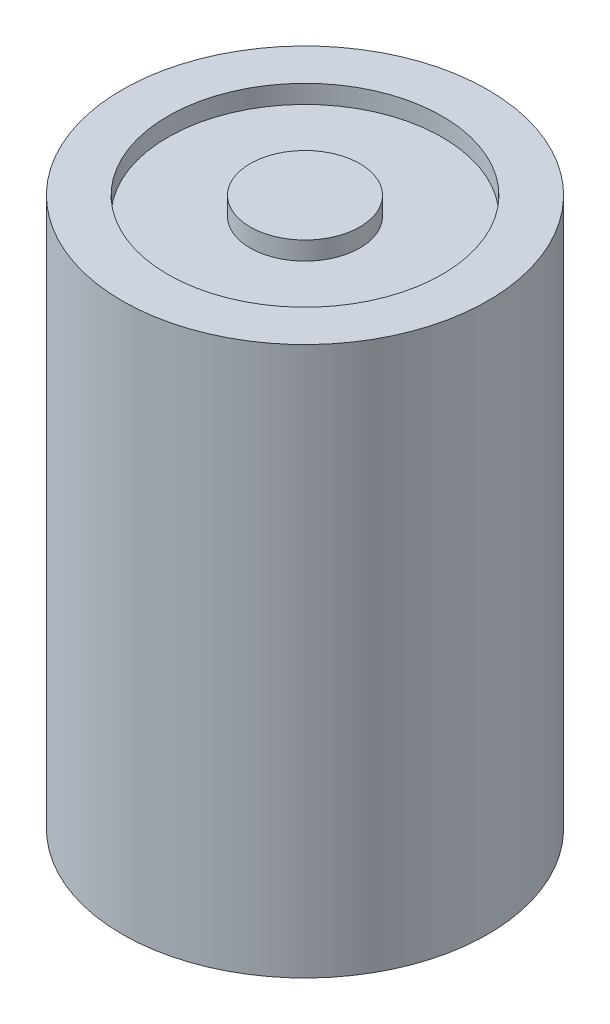
SolidWorks part; units mm, degrees
ref_plane "Front Plane" through (0, 0, 0) normal (0, 0, 1) x (1, 0, 0)
ref_plane "Top Plane" through (0, 0, 0) normal (0, 1, 0) x (1, 0, 0)
ref_plane "Right Plane" through (0, 0, 0) normal (1, 0, 0) x (0, 0, -1)
sketch "Sketch1" plane through (0, 0, 0) normal (0, 1, 0) x (1, 0, 0)
  circle A0 centre (0, 0) radius 10
  dimension "D1" = 20
extrude "Boss-Extrude1" add sketch "Sketch1" along normal blind 30
sketch "Sketch2" plane through (0, 30, 0) normal (0, 1, 0) x (1, 0, 0)
  circle A0 centre (0, 0) radius 3
  circle A1 centre (0, 0) radius 7.5
  dimension "D1" = 15
  dimension "D2" = 6
extrude "Cut-Extrude1" cut sketch "Sketch2" against normal blind 1
